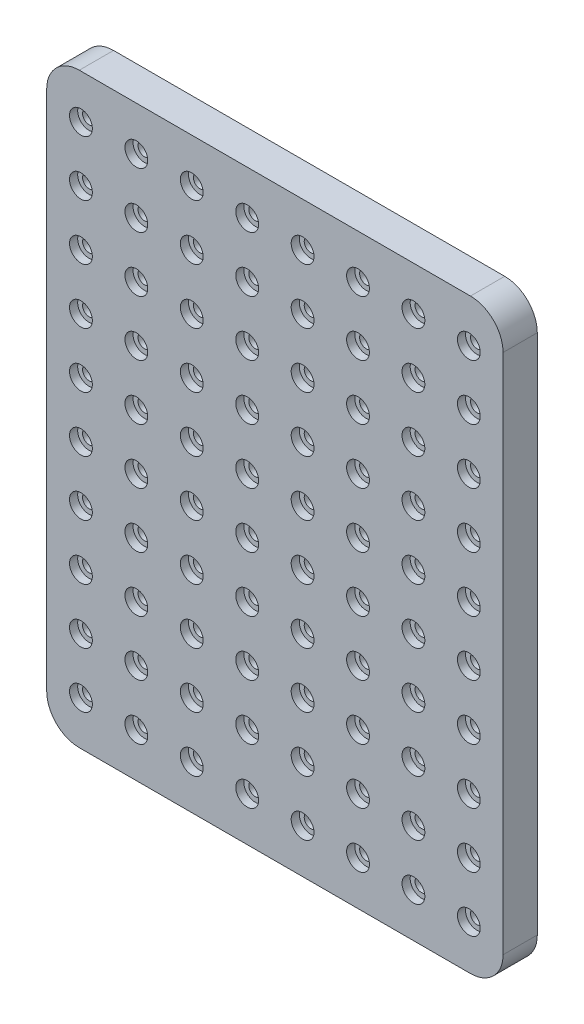
SolidWorks part; units mm, degrees
ref_plane "Ebene vorne" through (0, 0, 0) normal (0, 0, 1) x (1, 0, 0)
ref_plane "Ebene oben" through (0, 0, 0) normal (0, 1, 0) x (1, 0, 0)
ref_plane "Ebene rechts" through (0, 0, 0) normal (1, 0, 0) x (0, 0, -1)
sketch "Skizze1" plane through (0, 0, 0) normal (0, 0, 1) x (1, 0, 0)
  line L1 (0, 0) -> (140, 0)
  line L2 (0, 0) -> (0, 180)
  line L3 (0, 180) -> (140, 180)
  line L4 (140, 0) -> (140, 180)
  dimension "D1" = 180
  dimension "D2" = 140
extrude "Aufsatz-Linear austragen1" add sketch "Skizze1" along normal blind 10.5
sketch "Skizze2" plane through (0, 0, 10.5) normal (0, 0, 1) x (1, 0, 0)
  line L4 (0, 0) -> (140, 0) construction
  line L5 (70, 180) -> (70, 0) construction
  line L6 (140, 180) -> (0, 180) construction
  line L7 (0, 90) -> (140, 90) construction
  line L8 (0, 180) -> (0, 0) construction
  line L9 (140, 0) -> (140, 180) construction
  circle A0 centre (10.5, 183.5) radius 3.5
  circle A1 centre (27.5, 183.5) radius 3.5
  circle A2 centre (44.5, 183.5) radius 3.5
  circle A3 centre (61.5, 183.5) radius 3.5
  circle A4 centre (78.5, 183.5) radius 3.5
  circle A5 centre (95.5, 183.5) radius 3.5
  circle A6 centre (112.5, 183.5) radius 3.5
  circle A7 centre (129.5, 183.5) radius 3.5
  circle A8 centre (27.5, 166.5) radius 3.5
  circle A9 centre (44.5, 166.5) radius 3.5
  circle A10 centre (61.5, 166.5) radius 3.5
  circle A11 centre (78.5, 166.5) radius 3.5
  circle A12 centre (95.5, 166.5) radius 3.5
  circle A13 centre (112.5, 166.5) radius 3.5
  circle A14 centre (129.5, 166.5) radius 3.5
  circle A15 centre (27.5, 149.5) radius 3.5
  circle A16 centre (44.5, 149.5) radius 3.5
  circle A17 centre (61.5, 149.5) radius 3.5
  circle A18 centre (78.5, 149.5) radius 3.5
  circle A19 centre (95.5, 149.5) radius 3.5
  circle A20 centre (112.5, 149.5) radius 3.5
  circle A21 centre (129.5, 149.5) radius 3.5
  circle A22 centre (27.5, 132.5) radius 3.5
  circle A23 centre (44.5, 132.5) radius 3.5
  circle A24 centre (61.5, 132.5) radius 3.5
  circle A25 centre (78.5, 132.5) radius 3.5
  circle A26 centre (95.5, 132.5) radius 3.5
  circle A27 centre (112.5, 132.5) radius 3.5
  circle A28 centre (129.5, 132.5) radius 3.5
  circle A29 centre (27.5, 115.5) radius 3.5
  circle A30 centre (44.5, 115.5) radius 3.5
  circle A31 centre (61.5, 115.5) radius 3.5
  circle A32 centre (78.5, 115.5) radius 3.5
  circle A33 centre (95.5, 115.5) radius 3.5
  circle A34 centre (112.5, 115.5) radius 3.5
  circle A35 centre (129.5, 115.5) radius 3.5
  circle A36 centre (27.5, 98.5) radius 3.5
  circle A37 centre (44.5, 98.5) radius 3.5
  circle A38 centre (61.5, 98.5) radius 3.5
  circle A39 centre (78.5, 98.5) radius 3.5
  circle A40 centre (95.5, 98.5) radius 3.5
  circle A41 centre (112.5, 98.5) radius 3.5
  circle A42 centre (129.5, 98.5) radius 3.5
  circle A43 centre (27.5, 81.5) radius 3.5
  circle A44 centre (44.5, 81.5) radius 3.5
  circle A45 centre (61.5, 81.5) radius 3.5
  circle A46 centre (78.5, 81.5) radius 3.5
  circle A47 centre (95.5, 81.5) radius 3.5
  circle A48 centre (112.5, 81.5) radius 3.5
  circle A49 centre (129.5, 81.5) radius 3.5
  circle A50 centre (27.5, 64.5) radius 3.5
  circle A51 centre (44.5, 64.5) radius 3.5
  circle A52 centre (61.5, 64.5) radius 3.5
  circle A53 centre (78.5, 64.5) radius 3.5
  circle A54 centre (95.5, 64.5) radius 3.5
  circle A55 centre (112.5, 64.5) radius 3.5
  circle A56 centre (129.5, 64.5) radius 3.5
  circle A57 centre (27.5, 47.5) radius 3.5
  circle A58 centre (44.5, 47.5) radius 3.5
  circle A59 centre (61.5, 47.5) radius 3.5
  circle A60 centre (78.5, 47.5) radius 3.5
  circle A61 centre (95.5, 47.5) radius 3.5
  circle A62 centre (112.5, 47.5) radius 3.5
  circle A63 centre (129.5, 47.5) radius 3.5
  circle A64 centre (27.5, 30.5) radius 3.5
  circle A65 centre (44.5, 30.5) radius 3.5
  circle A66 centre (61.5, 30.5) radius 3.5
  circle A67 centre (78.5, 30.5) radius 3.5
  circle A68 centre (95.5, 30.5) radius 3.5
  circle A69 centre (112.5, 30.5) radius 3.5
  circle A70 centre (129.5, 30.5) radius 3.5
  circle A71 centre (27.5, 13.5) radius 3.5
  circle A72 centre (44.5, 13.5) radius 3.5
  circle A73 centre (61.5, 13.5) radius 3.5
  circle A74 centre (78.5, 13.5) radius 3.5
  circle A75 centre (95.5, 13.5) radius 3.5
  circle A76 centre (112.5, 13.5) radius 3.5
  circle A77 centre (129.5, 13.5) radius 3.5
  circle A85 centre (10.5, 166.5) radius 3.5
  circle A86 centre (10.5, 149.5) radius 3.5
  circle A87 centre (10.5, 132.5) radius 3.5
  circle A88 centre (10.5, 115.5) radius 3.5
  circle A89 centre (10.5, 98.5) radius 3.5
  circle A90 centre (10.5, 81.5) radius 3.5
  circle A91 centre (10.5, 64.5) radius 3.5
  circle A92 centre (10.5, 47.5) radius 3.5
  circle A93 centre (10.5, 30.5) radius 3.5
  circle A94 centre (10.5, 13.5) radius 3.5
  dimension "D1" = 7
  dimension "D2" = 17
  dimension "D3" = 17
  dimension "D4" = 8
  dimension "D5" = 11
extrude "Schnitt-Linear austragen3" cut sketch "Skizze2" against normal blind 2.5
sketch "Skizze3" plane through (0, 0, 0) normal (0, 0, 1) x (1, 0, 0)
  line L0 (140, 0) -> (140, 180) construction
  line L1 (140, 180) -> (0, 180) construction
  line L5 (70, 200) -> (70, 0) construction
  line L7 (0, 90) -> (140, 90) construction
  circle A0 centre (10.5, 183.5) radius 2
  circle A1 centre (27.5, 183.5) radius 2
  circle A2 centre (44.5, 183.5) radius 2
  circle A3 centre (61.5, 183.5) radius 2
  circle A4 centre (78.5, 183.5) radius 2
  circle A5 centre (95.5, 183.5) radius 2
  circle A6 centre (112.5, 183.5) radius 2
  circle A7 centre (129.5, 183.5) radius 2
  circle A8 centre (27.5, 166.5) radius 2
  circle A9 centre (44.5, 166.5) radius 2
  circle A10 centre (61.5, 166.5) radius 2
  circle A11 centre (78.5, 166.5) radius 2
  circle A12 centre (95.5, 166.5) radius 2
  circle A13 centre (112.5, 166.5) radius 2
  circle A14 centre (129.5, 166.5) radius 2
  circle A15 centre (27.5, 149.5) radius 2
  circle A16 centre (44.5, 149.5) radius 2
  circle A17 centre (61.5, 149.5) radius 2
  circle A18 centre (78.5, 149.5) radius 2
  circle A19 centre (95.5, 149.5) radius 2
  circle A20 centre (112.5, 149.5) radius 2
  circle A21 centre (129.5, 149.5) radius 2
  circle A22 centre (27.5, 132.5) radius 2
  circle A23 centre (44.5, 132.5) radius 2
  circle A24 centre (61.5, 132.5) radius 2
  circle A25 centre (78.5, 132.5) radius 2
  circle A26 centre (95.5, 132.5) radius 2
  circle A27 centre (112.5, 132.5) radius 2
  circle A28 centre (129.5, 132.5) radius 2
  circle A29 centre (27.5, 115.5) radius 2
  circle A30 centre (44.5, 115.5) radius 2
  circle A31 centre (61.5, 115.5) radius 2
  circle A32 centre (78.5, 115.5) radius 2
  circle A33 centre (95.5, 115.5) radius 2
  circle A34 centre (112.5, 115.5) radius 2
  circle A35 centre (129.5, 115.5) radius 2
  circle A36 centre (27.5, 98.5) radius 2
  circle A37 centre (44.5, 98.5) radius 2
  circle A38 centre (61.5, 98.5) radius 2
  circle A39 centre (78.5, 98.5) radius 2
  circle A40 centre (95.5, 98.5) radius 2
  circle A41 centre (112.5, 98.5) radius 2
  circle A42 centre (129.5, 98.5) radius 2
  circle A43 centre (27.5, 81.5) radius 2
  circle A44 centre (44.5, 81.5) radius 2
  circle A45 centre (61.5, 81.5) radius 2
  circle A46 centre (78.5, 81.5) radius 2
  circle A47 centre (95.5, 81.5) radius 2
  circle A48 centre (112.5, 81.5) radius 2
  circle A49 centre (129.5, 81.5) radius 2
  circle A50 centre (27.5, 64.5) radius 2
  circle A51 centre (44.5, 64.5) radius 2
  circle A52 centre (61.5, 64.5) radius 2
  circle A53 centre (78.5, 64.5) radius 2
  circle A54 centre (95.5, 64.5) radius 2
  circle A55 centre (112.5, 64.5) radius 2
  circle A56 centre (129.5, 64.5) radius 2
  circle A57 centre (27.5, 47.5) radius 2
  circle A58 centre (44.5, 47.5) radius 2
  circle A59 centre (61.5, 47.5) radius 2
  circle A60 centre (78.5, 47.5) radius 2
  circle A61 centre (95.5, 47.5) radius 2
  circle A62 centre (112.5, 47.5) radius 2
  circle A63 centre (129.5, 47.5) radius 2
  circle A64 centre (27.5, 30.5) radius 2
  circle A65 centre (44.5, 30.5) radius 2
  circle A66 centre (61.5, 30.5) radius 2
  circle A67 centre (78.5, 30.5) radius 2
  circle A68 centre (95.5, 30.5) radius 2
  circle A69 centre (112.5, 30.5) radius 2
  circle A70 centre (129.5, 30.5) radius 2
  circle A71 centre (27.5, 13.5) radius 2
  circle A72 centre (44.5, 13.5) radius 2
  circle A73 centre (61.5, 13.5) radius 2
  circle A74 centre (78.5, 13.5) radius 2
  circle A75 centre (95.5, 13.5) radius 2
  circle A76 centre (112.5, 13.5) radius 2
  circle A77 centre (129.5, 13.5) radius 2
  circle A78 centre (27.5, -3.5) radius 2
  circle A79 centre (44.5, -3.5) radius 2
  circle A80 centre (61.5, -3.5) radius 2
  circle A81 centre (78.5, -3.5) radius 2
  circle A82 centre (95.5, -3.5) radius 2
  circle A83 centre (112.5, -3.5) radius 2
  circle A84 centre (129.5, -3.5) radius 2
  circle A85 centre (10.5, 166.5) radius 2
  circle A86 centre (10.5, 149.5) radius 2
  circle A87 centre (10.5, 132.5) radius 2
  circle A88 centre (10.5, 115.5) radius 2
  circle A89 centre (10.5, 98.5) radius 2
  circle A90 centre (10.5, 81.5) radius 2
  circle A91 centre (10.5, 64.5) radius 2
  circle A92 centre (10.5, 47.5) radius 2
  circle A93 centre (10.5, 30.5) radius 2
  circle A94 centre (10.5, 13.5) radius 2
  circle A95 centre (10.5, -3.5) radius 2
  point P199 (140, 90)
  point P202 (70, 180)
  dimension "D1" = 4
  dimension "D3" = 17
  dimension "17" = 17
  dimension "D4" = 8
  dimension "D5" = 12
extrude "Schnitt-Linear austragen5" cut sketch "Skizze3" along normal through all
fillet "Verrundung1" radius 10 4 edges at (140, 0, 5.25) (0, 0, 5.25) (0, 180, 5.25) (140, 180, 5.25)
sketch "Skizze5" plane through (0, 0, 10.5) normal (0, 0, 1) x (1, 0, 0)
  line L0 (44.5, 98.5) -> (112.5, 98.5)
  line L7 (36.8867, 107.9591) -> (121.8867, 107.9591)
  line L10 (36.8867, 107.9591) -> (36.8867, 51.9591)
  line L11 (36.8867, 51.9591) -> (121.8867, 51.9591)
  line L12 (121.8867, 107.9591) -> (121.8867, 51.9591)
  line L13 (112.5, 98.5) -> (112.5, 64.5)
  line L14 (112.5, 64.5) -> (112.5, 98.5)
  dimension "D1" = 56
  dimension "D2" = 85
